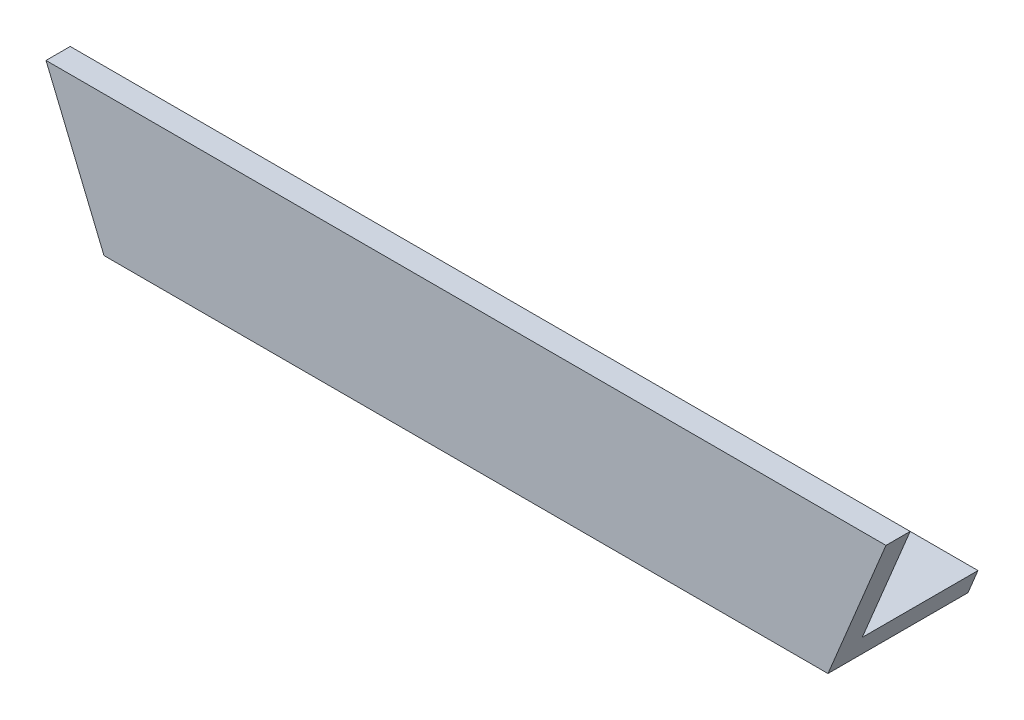
SolidWorks part; units mm, degrees
ref_plane "Front Plane" through (0, 0, 0) normal (0, 0, 1) x (1, 0, 0)
ref_plane "Top Plane" through (0, 0, 0) normal (0, 1, 0) x (1, 0, 0)
ref_plane "Right Plane" through (0, 0, 0) normal (1, 0, 0) x (0, 0, -1)
sketch "Sketch1" plane through (0, 0, 0) normal (1, 0, 0) x (0, 0, -1)
  line L0 (0, 0) -> (20, 0)
  line L1 (20, 0) -> (20, 3.4612)
  line L2 (20, 3.4612) -> (3.4612, 3.4612)
  line L3 (3.4612, 3.4612) -> (3.4612, 20)
  line L4 (3.4612, 20) -> (0, 20)
  line L5 (0, 20) -> (0, 0)
  dimension "D1" = 3.4612
  dimension "D2" = 20
extrude "Boss-Extrude1" add sketch "Sketch1" along normal blind 120
sketch "Sketch2" plane through (0, 0, 0) normal (0, 0, -1) x (1, 0, 0)
  line L7 (120, -20) -> (120, 0)
  line L9 (0, -20) -> (0, 0)
  line L10 (0, -20) -> (8.2843, 0)
  line L11 (120, 0) -> (0, 0) construction
  line L12 (8.2843, 0) -> (0, 0)
  line L13 (120, -20) -> (111.7157, 0)
  line L14 (111.7157, 0) -> (120, 0)
  dimension "D1" = 22.5
extrude "Cut-Extrude1" cut sketch "Sketch2" along normal through all
